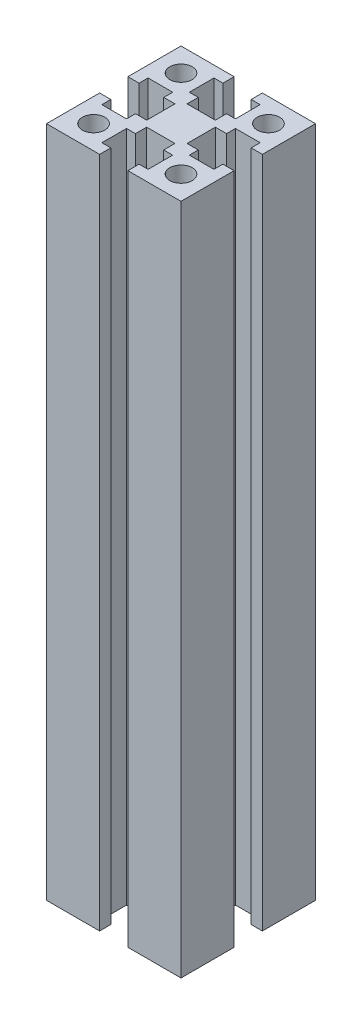
SolidWorks part; units mm, degrees
ref_plane "前视基准面" through (0, 0, 0) normal (0, 0, 1) x (1, 0, 0)
ref_plane "上视基准面" through (0, 0, 0) normal (0, 1, 0) x (1, 0, 0)
ref_plane "右视基准面" through (0, 0, 0) normal (1, 0, 0) x (0, 0, -1)
sketch "草图1" plane through (0, 0, 0) normal (0, 1, 0) x (1, 0, 0)
  line L0 (-15, -3.15) -> (-12.5, -3.15)
  line L1 (-15, 15) -> (-3.15, 15)
  line L2 (-15, 15) -> (-15, 3.15)
  line L3 (-15, -15) -> (-3.15, -15)
  line L4 (15, 15) -> (15, 3.15)
  line L5 (-15, 15) -> (15, -15) construction
  line L6 (-15, -15) -> (15, 15) construction
  line L7 (-12.5, -3.15) -> (-12.5, -5.15)
  line L8 (-12.5, -5.15) -> (-7, -5.15)
  line L9 (-7, -5.15) -> (-7, -3.15)
  line L10 (-7, -3.15) -> (-4.5, -3.15)
  line L11 (-4.5, -3.15) -> (-4.5, 3.15)
  line L12 (-4.5, 3.15) -> (-7, 3.15)
  line L13 (-7, 3.15) -> (-7, 5.15)
  line L14 (-7, 5.15) -> (-12.5, 5.15)
  line L15 (-12.5, 5.15) -> (-12.5, 3.15)
  line L16 (-12.5, 3.15) -> (-15, 3.15)
  line L17 (-15, 0) -> (-4.5, 0) construction
  line L18 (-15, -3.15) -> (-15, -15)
  line L19 (-15, 3.15) -> (-15, 0) construction
  line L20 (-15, 0) -> (-15, -3.15) construction
  line L21 (3.15, 12.5) -> (3.15, 15)
  line L22 (5.15, 12.5) -> (3.15, 12.5)
  line L23 (5.15, 7) -> (5.15, 12.5)
  line L24 (3.15, 7) -> (5.15, 7)
  line L25 (3.15, 4.5) -> (3.15, 7)
  line L26 (-3.15, 4.5) -> (3.15, 4.5)
  line L27 (-3.15, 7) -> (-3.15, 4.5)
  line L28 (-5.15, 7) -> (-3.15, 7)
  line L29 (-5.15, 12.5) -> (-5.15, 7)
  line L30 (-3.15, 12.5) -> (-5.15, 12.5)
  line L31 (-3.15, 15) -> (-3.15, 12.5)
  line L32 (12.5, -3.15) -> (15, -3.15)
  line L33 (12.5, -5.15) -> (12.5, -3.15)
  line L34 (7, -5.15) -> (12.5, -5.15)
  line L35 (7, -3.15) -> (7, -5.15)
  line L36 (4.5, -3.15) -> (7, -3.15)
  line L37 (4.5, 3.15) -> (4.5, -3.15)
  line L38 (7, 3.15) -> (4.5, 3.15)
  line L39 (7, 5.15) -> (7, 3.15)
  line L40 (12.5, 5.15) -> (7, 5.15)
  line L41 (12.5, 3.15) -> (12.5, 5.15)
  line L42 (15, 3.15) -> (12.5, 3.15)
  line L43 (-3.15, -12.5) -> (-3.15, -15)
  line L44 (-5.15, -12.5) -> (-3.15, -12.5)
  line L45 (-5.15, -7) -> (-5.15, -12.5)
  line L46 (-3.15, -7) -> (-5.15, -7)
  line L47 (-3.15, -4.5) -> (-3.15, -7)
  line L48 (3.15, -4.5) -> (-3.15, -4.5)
  line L49 (3.15, -7) -> (3.15, -4.5)
  line L50 (5.15, -7) -> (3.15, -7)
  line L51 (5.15, -12.5) -> (5.15, -7)
  line L52 (3.15, -12.5) -> (5.15, -12.5)
  line L53 (3.15, -15) -> (3.15, -12.5)
  line L54 (3.15, 15) -> (15, 15)
  line L55 (15, -3.15) -> (15, -15)
  line L56 (3.15, -15) -> (15, -15)
  line L57 (-5.15, -9.75) -> (-15, -9.75) construction
  line L58 (-9.75, -5.15) -> (-9.75, -15) construction
  circle A0 centre (-9.75, -9.75) radius 2.5
  circle A1 centre (-9.75, 9.75) radius 2.5
  circle A2 centre (9.75, 9.75) radius 2.5
  circle A3 centre (9.75, -9.75) radius 2.5
  point P0 (0, 0)
  point P59 (0, 0)
  point P72 (0, 0)
  dimension "D1" = 5
  dimension "D2" = 6.3
  dimension "D3" = 10.3
  dimension "D4" = 2.5
  dimension "D5" = 5.5
  dimension "D6" = 10.5
  dimension "D7" = 30
  dimension "D8" = 4
  dimension "D9" = 4
extrude "凸台-拉伸1" add sketch "草图1" along normal mid plane 360
sketch "草图2" plane through (0, 180, 0) normal (0, 1, 0) x (1, 0, 0)
  circle A0 centre (0, 0) radius 82.2505
extrude "切除-拉伸1" cut sketch "草图2" against normal blind 10
sketch "草图3" plane through (0, -180, 0) normal (0, -1, 0) x (1, 0, 0)
  circle A0 centre (0.2164, -1.772) radius 47.3598
extrude "切除-拉伸2" cut sketch "草图3" against normal blind 200
equation "\"零件重量\"= \"SW-质量\" / 1000"
